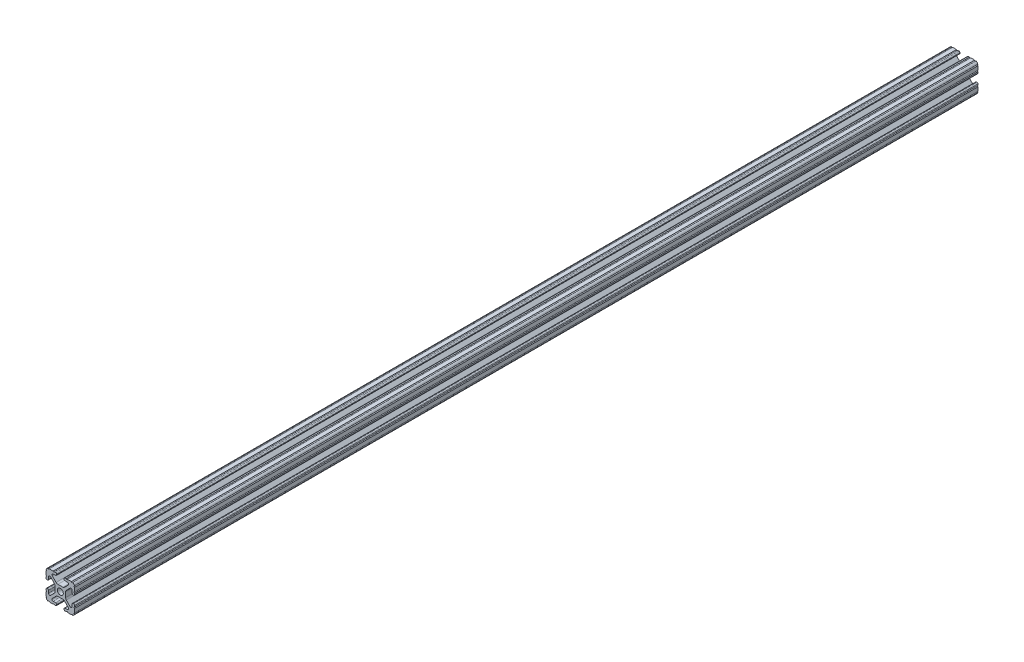
SolidWorks part; units mm, degrees
ref_plane "Front Plane" through (0, 0, 0) normal (0, 0, 1) x (1, 0, 0)
ref_plane "Top Plane" through (0, 0, 0) normal (0, 1, 0) x (1, 0, 0)
ref_plane "Right Plane" through (0, 0, 0) normal (1, 0, 0) x (0, 0, -1)
sketch "Sketch2" plane through (0, 0, 0) normal (0, 0, 1) x (1, 0, 0)
  line L0 (0, 12.7) -> (0, -12.7) construction
  line L1 (-12.7, 0) -> (12.7, 0) construction
  line L2 (3.2512, -12.7) -> (12.7, -12.7)
  line L3 (12.7, -12.7) -> (12.7, -3.2512)
  line L4 (3.2512, -12.7) -> (3.2512, -10.4902)
  line L5 (3.2512, -10.4902) -> (8.9276, -10.4902)
  line L6 (8.9276, -10.4902) -> (3.0856, -4.6482)
  line L7 (0, 0) -> (12.7, -12.7) construction
  line L8 (12.7, -3.2512) -> (10.4902, -3.2512)
  line L9 (10.4902, -3.2512) -> (10.4902, -8.9276)
  line L10 (10.4902, -8.9276) -> (4.6482, -3.0856)
  circle A0 centre (0, 0) radius 2.6035
  arc A1 (6.3485, -10.4902) -> (7.1039, -8.6665) centre (6.3485, -9.4219) ccw construction
  point P8 (0, -4.6482)
  dimension "Center Hole Diameter" = 5.207
  dimension "Rail Height" = 25.4
  dimension "Rail Width" = 25.4
  dimension "T-Slot Width" = 6.5024
  dimension "Slot Inner Width" = 14.8336
  dimension "Thickness" = 2.2098
  dimension "Slot Depth" = 5.842
  dimension "D1" = 2.2098
sketch "Sketch3" plane through (0, 0, 0) normal (1, 0, 0) x (0, 0, -1)
  line L0 (-400.05, -12.7) -> (400.05, -12.7) construction
  line L1 (-374.65, 0) -> (374.65, 0) construction
  dimension "Length" = 800.1
  dimension "D1" = 25.4
sketch "Sketch4" plane through (0, 0, 0) normal (0, 0, 1) x (1, 0, 0)
  line L0 (4.1904, -12.7) -> (10.1173, -12.7)
  line L1 (3.2512, -12.7) -> (12.7, -12.7) construction
  line L2 (3.2512, -12.7) -> (3.2512, -10.4902) construction
  line L3 (3.2512, -10.4902) -> (8.9276, -10.4902) construction
  line L4 (3.2512, -11.4294) -> (3.2512, -11.7608)
  line L5 (4.1904, -10.4902) -> (6.3485, -10.4902)
  line L6 (0, -4.6482) -> (2.164, -4.6482)
  line L7 (8.9276, -10.4902) -> (3.0856, -4.6482) construction
  line L8 (3.7373, -5.2999) -> (7.1039, -8.6665)
  line L9 (12.7, -12.7) -> (12.7, -3.2512) construction
  line L10 (10.4902, -8.9276) -> (4.6482, -3.0856) construction
  line L11 (10.4902, -3.2512) -> (10.4902, -8.9276) construction
  line L12 (10.4902, -6.3485) -> (10.4902, -4.1904)
  line L13 (12.7, -3.2512) -> (10.4902, -3.2512) construction
  line L14 (11.4294, -3.2512) -> (11.7608, -3.2512)
  line L15 (12.7, -4.1904) -> (12.7, -10.1173)
  line L16 (8.6665, -7.1039) -> (5.2999, -3.7373)
  line L17 (4.6482, 0) -> (4.6482, -2.164)
  line L18 (-12.7, 0) -> (12.7, 0) construction
  line L19 (0, -4.6482) -> (0, -2.6035)
  line L20 (0, 12.7) -> (0, -12.7) construction
  line L21 (4.6482, 0) -> (2.6035, 0)
  arc A0 (3.2512, -11.7608) -> (4.1904, -12.7) centre (4.1904, -11.7608) ccw
  arc A2 (3.2512, -11.4294) -> (4.1904, -10.4902) centre (4.1904, -11.4294) cw
  arc A3 (6.3485, -10.4902) -> (7.1039, -8.6665) centre (6.3485, -9.4219) ccw
  arc A4 (2.164, -4.6482) -> (3.7373, -5.2999) centre (2.164, -6.8732) cw
  arc A5 (10.1173, -12.7) -> (12.7, -10.1173) centre (10.1173, -10.1173) ccw
  arc A6 (8.6665, -7.1039) -> (10.4902, -6.3485) centre (9.4219, -6.3485) ccw
  arc A7 (10.4902, -4.1904) -> (11.4294, -3.2512) centre (11.4294, -4.1904) cw
  arc A8 (11.7608, -3.2512) -> (12.7, -4.1904) centre (11.7608, -4.1904) cw
  arc A9 (5.2999, -3.7373) -> (4.6482, -2.164) centre (6.8732, -2.164) cw
  circle A10 centre (0, 0) radius 2.6035 construction
  arc A11 (0, -2.6035) -> (2.6035, 0) centre (0, 0) ccw
  dimension "D1" = 2.5827
  dimension "D2" = 2.225
  dimension "D3" = 0.9392
extrude "Boss-Extrude1" add sketch "Sketch4" along normal mid plane 800.1
sketch "Sketch5" plane through (0, 0, 0) normal (0, 0, 1) x (1, 0, 0)
  line L0 (3.2512, -12.7) -> (12.7, -12.7) construction
  line L1 (4.1904, -10.4902) -> (6.3485, -10.4902) construction
  line L3 (0, 0) -> (12.7, -12.7) construction
  line L4 (6.3485, -10.4902) -> (6.3485, -12.7) construction
  line L5 (8.9276, -10.4902) -> (3.0856, -4.6482) construction
  circle A0 centre (10.3562, -12.7) radius 0.5524
  circle A1 centre (5.796, -12.7) radius 0.5524
  circle A2 centre (12.7, -10.3562) radius 0.5524
  circle A3 centre (12.7, -5.796) radius 0.5524
  point P10 (5.2694, -10.4902)
  point P12 (9.4219, -6.3485)
  dimension "D1" = 1.1049
extrude "Cut-Extrude1" cut sketch "Sketch5" against normal through all both and the other way through all
mirror "Mirror1" about plane through (0, 0, 0) normal (1, 0, 0) of bodies 137 134
mirror "Mirror2" about plane through (0, 0, 0) normal (0, 1, 0) of bodies 135
equation "\"D1@Boss-Extrude1\"=\"Length@Sketch3\""
equation "\"D1@Sketch2\"=\"Thickness@Sketch2\""
equation "\"D2@Sketch4\"=\"Slot Inner Width@Sketch2\"*0.15"
equation "\"D1@Sketch4\"=\"D3@Sketch4\"*2.75"
equation "\"D3@Sketch4\"=\"Thickness@Sketch2\"*0.425"
equation "\"D1@Sketch5\"=\"Thickness@Sketch2\"*0.5"
